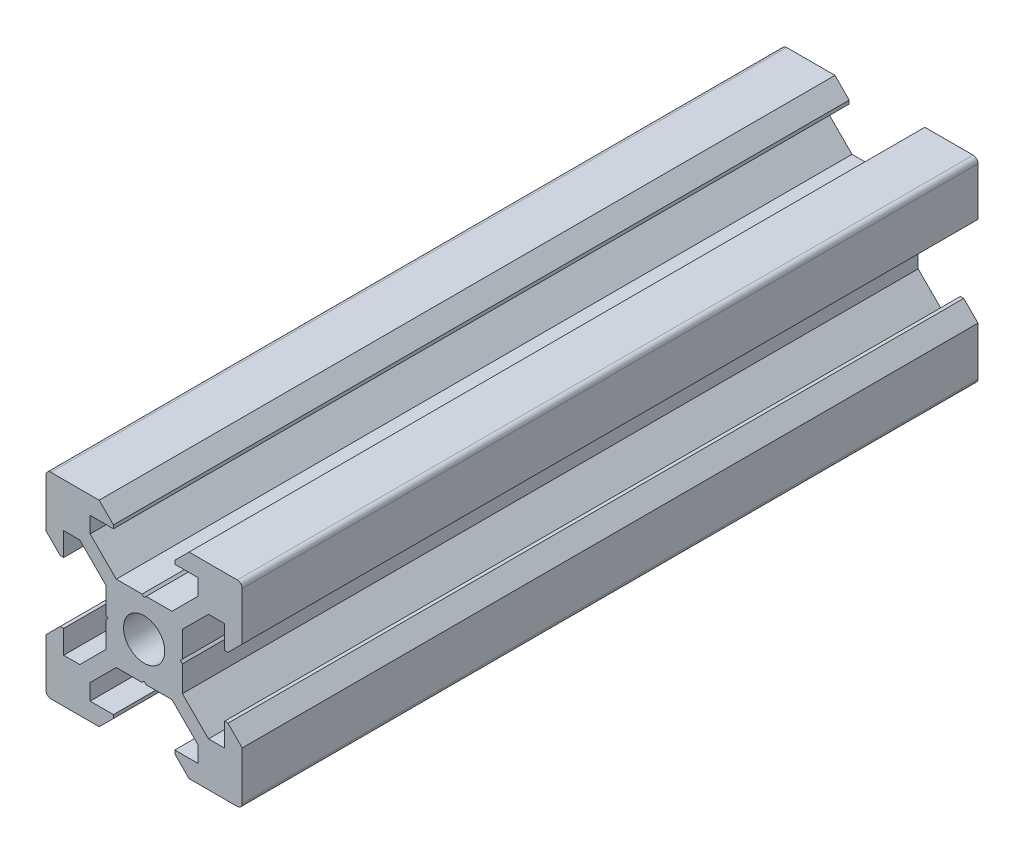
SolidWorks part; units mm, degrees
material "6061-T6 (SS)"
ref_plane "Front Plane" through (0, 0, 0) normal (0, 0, 1) x (1, 0, 0)
ref_plane "Top Plane" through (0, 0, 0) normal (0, 1, 0) x (1, 0, 0)
ref_plane "Right Plane" through (0, 0, 0) normal (1, 0, 0) x (0, 0, -1)
sketch "Sketch1" plane through (0, 0, 0) normal (0, 0, 1) x (1, 0, 0)
  line L1 (9.5, -10) -> (-9.5, -10)
  line L2 (10, -9.5) -> (10, 9.5)
  line L3 (9.5, 10) -> (-9.5, 10)
  line L4 (-10, -9.5) -> (-10, 9.5)
  line L5 (10, -10) -> (-10, 10) construction
  line L6 (10, 10) -> (-10, -10) construction
  circle A0 centre (0, 0) radius 2.1
  arc A1 (-9.5, 10) -> (-10, 9.5) centre (-9.5, 9.5) ccw
  arc A2 (10, 9.5) -> (9.5, 10) centre (9.5, 9.5) ccw
  arc A3 (9.5, -10) -> (10, -9.5) centre (9.5, -9.5) ccw
  arc A4 (-9.5, -10) -> (-10, -9.5) centre (-9.5, -9.5) cw
  point P0 (0, 0)
  line B0 (0, 0) -> (0, 10) construction
  line B1 (0, 3.69) -> (-0.21, 3.9)
  line B2 (-0.21, 3.9) -> (-2.8393, 3.9)
  line B3 (-2.8393, 3.9) -> (-5.5, 6.5607)
  line B4 (-5.5, 6.5607) -> (-5.5, 8.2)
  line B5 (-5.5, 8.2) -> (-3.125, 8.2)
  line B6 (-3.125, 8.2) -> (-3.125, 8.545)
  line B7 (-3.125, 8.545) -> (-4.58, 10)
  line B8 (-4.58, 10) -> (4.58, 10)
  line B9 (0, 0) -> (-5.9132, 5.9132) construction
  line B10 (3.125, 8.545) -> (4.58, 10)
  line B11 (3.125, 8.2) -> (3.125, 8.545)
  line B12 (5.5, 8.2) -> (3.125, 8.2)
  line B13 (5.5, 6.5607) -> (5.5, 8.2)
  line B14 (2.8393, 3.9) -> (5.5, 6.5607)
  line B15 (0.21, 3.9) -> (2.8393, 3.9)
  line B16 (0, 3.69) -> (0.21, 3.9)
  line B17 (0, 0) -> (-10, 0) construction
  line B18 (-3.69, 0) -> (-3.9, -0.21)
  line B19 (-3.9, -0.21) -> (-3.9, -2.8393)
  line B20 (-3.9, -2.8393) -> (-6.5607, -5.5)
  line B21 (-6.5607, -5.5) -> (-8.2, -5.5)
  line B22 (-8.2, -5.5) -> (-8.2, -3.125)
  line B23 (-8.2, -3.125) -> (-8.545, -3.125)
  line B24 (-8.545, -3.125) -> (-10, -4.58)
  line B25 (-10, -4.58) -> (-10, 4.58)
  line B26 (0, 0) -> (-5.9132, -5.9132) construction
  line B27 (-8.545, 3.125) -> (-10, 4.58)
  line B28 (-8.2, 3.125) -> (-8.545, 3.125)
  line B29 (-8.2, 5.5) -> (-8.2, 3.125)
  line B30 (-6.5607, 5.5) -> (-8.2, 5.5)
  line B31 (-3.9, 2.8393) -> (-6.5607, 5.5)
  line B32 (-3.9, 0.21) -> (-3.9, 2.8393)
  line B33 (-3.69, 0) -> (-3.9, 0.21)
  line B34 (0, 0) -> (0, -10) construction
  line B35 (0, -3.69) -> (0.21, -3.9)
  line B36 (0.21, -3.9) -> (2.8393, -3.9)
  line B37 (2.8393, -3.9) -> (5.5, -6.5607)
  line B38 (5.5, -6.5607) -> (5.5, -8.2)
  line B39 (5.5, -8.2) -> (3.125, -8.2)
  line B40 (3.125, -8.2) -> (3.125, -8.545)
  line B41 (3.125, -8.545) -> (4.58, -10)
  line B42 (4.58, -10) -> (-4.58, -10)
  line B43 (0, 0) -> (5.9132, -5.9132) construction
  line B44 (-3.125, -8.545) -> (-4.58, -10)
  line B45 (-3.125, -8.2) -> (-3.125, -8.545)
  line B46 (-5.5, -8.2) -> (-3.125, -8.2)
  line B47 (-5.5, -6.5607) -> (-5.5, -8.2)
  line B48 (-2.8393, -3.9) -> (-5.5, -6.5607)
  line B49 (-0.21, -3.9) -> (-2.8393, -3.9)
  line B50 (0, -3.69) -> (-0.21, -3.9)
  line B51 (0, 0) -> (10, 0) construction
  line B52 (3.69, 0) -> (3.9, 0.21)
  line B53 (3.9, 0.21) -> (3.9, 2.8393)
  line B54 (3.9, 2.8393) -> (6.5607, 5.5)
  line B55 (6.5607, 5.5) -> (8.2, 5.5)
  line B56 (8.2, 5.5) -> (8.2, 3.125)
  line B57 (8.2, 3.125) -> (8.545, 3.125)
  line B58 (8.545, 3.125) -> (10, 4.58)
  line B59 (10, 4.58) -> (10, -4.58)
  line B60 (0, 0) -> (5.9132, 5.9132) construction
  line B61 (8.545, -3.125) -> (10, -4.58)
  line B62 (8.2, -3.125) -> (8.545, -3.125)
  line B63 (8.2, -5.5) -> (8.2, -3.125)
  line B64 (6.5607, -5.5) -> (8.2, -5.5)
  line B65 (3.9, -2.8393) -> (6.5607, -5.5)
  line B66 (3.9, -0.21) -> (3.9, -2.8393)
  line B67 (3.69, 0) -> (3.9, -0.21)
  dimension "D1" = 4.2
  dimension "D3" = 0.5
  dimension "D2" = 20
sketch_block_instance "V Slot 1-4"
sketch_block "V Slot 1" parameters "D1"=10, "D2"=11, "D3"=4.3, "D4"=1.8, "D5"=0.21, "D6"=45, "D7"=9.16, "D8"=1.5, "D9"=6.25
sketch_block_instance "V Slot 1-5"
sketch_block_instance "V Slot 1-6"
sketch_block_instance "V Slot 1-7"
extrude "Boss-Extrude1" add sketch "Sketch1" along normal blind 75 contours B67 B52 B53 B54 B55 B56 B57 B58 L2 A2 L3 B10 B11 B12 B13 B14 B15 B16 B1 B2 B3 B4 B5 B6 B7 A1 L4 B27 B28 B29 B30 B31 B32 B33 B18 B19 B20 B21 B22 B23 B24 A4 L1 B44 B45 B46 B47 B48 B49
